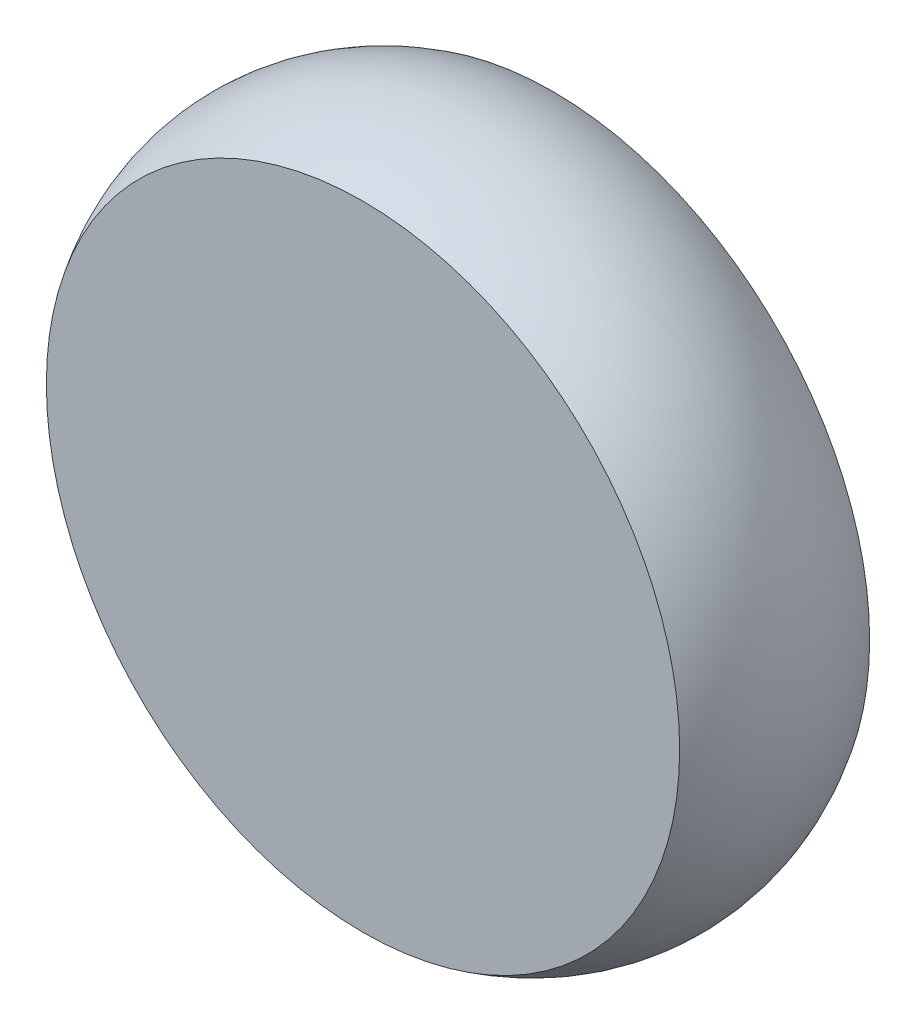
SolidWorks part; units mm, degrees
ref_plane "Front Plane" through (0, 0, 0) normal (0, 0, 1) x (1, 0, 0)
ref_plane "Top Plane" through (0, 0, 0) normal (0, 1, 0) x (1, 0, 0)
ref_plane "Right Plane" through (0, 0, 0) normal (1, 0, 0) x (0, 0, -1)
sketch "Sketch1" plane through (0, 0, 0) normal (1, 0, 0) x (0, 0, -1)
  line L0 (0, 0) -> (0, 10)
  line L1 (150, 0) -> (150, 10)
  line L2 (6, 10) -> (150, 10)
  line L3 (0, 250) -> (40, 250) construction
  line L4 (0, 10) -> (0, 250)
  line L5 (0, 250) -> (6, 250)
  line L6 (6, 250) -> (6, 10)
  arc A2 (0, 0) -> (150, 0) centre (75, 118.2159) ccw
  dimension "D2" = 140
  dimension "D1" = 10
  dimension "D3" = 150
  dimension "D4" = 250
  dimension "D5" = 6
revolve "Revolve1" add sketch "Sketch1" angle 360 about L3
sketch "Sketch2" plane through (0, 0, -6) normal (0, 0, -1) x (-1, 0, 0)
  circle A0 centre (0, 250) radius 50
  dimension "D1" = 100
extrude "Boss-Extrude1" add sketch "Sketch2" along normal blind 100
sketch "Sketch3" plane through (0, 0, -106) normal (0, 0, -1) x (-1, 0, 0)
  circle A2 centre (0, 250) radius 30
  circle A3 centre (0, 250) radius 30
  dimension "D1" = 20
extrude "Boss-Extrude2" add sketch "Sketch3" along normal blind 50
sketch "Sketch4" plane through (0, 0, -156) normal (0, 0, -1) x (-1, 0, 0)
  circle A2 centre (0, 250) radius 20
  circle A3 centre (0, 250) radius 20
  dimension "D1" = 10
extrude "Cut-Extrude1" cut sketch "Sketch4" against normal blind 30
